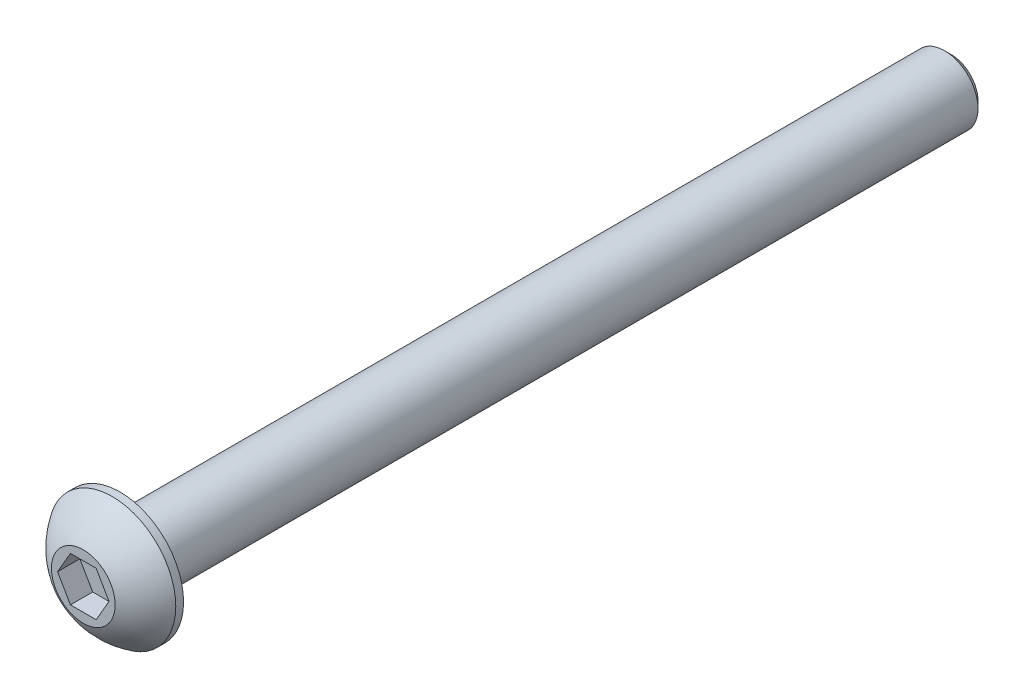
SolidWorks part; units mm, degrees
ref_plane "前视基准面" through (0, 0, 0) normal (0, 0, 1) x (1, 0, 0)
ref_plane "上视基准面" through (0, 0, 0) normal (0, 1, 0) x (1, 0, 0)
ref_plane "右视基准面" through (0, 0, 0) normal (1, 0, 0) x (0, 0, -1)
sketch "草图1" plane through (0, 0, 0) normal (1, 0, 0) x (0, 0, -1)
  line L0 (0, 1.5) -> (0, 2.85)
  line L1 (0, 2.85) -> (-0.35, 2.85)
  line L2 (0, 0) -> (-1.65, 0)
  line L3 (-1.65, 0) -> (-1.65, 1.43)
  line L4 (0, 0) -> (37.3, 0)
  line L5 (37.3, 0) -> (37.3, 1.5)
  line L6 (37.3, 1.5) -> (0, 1.5)
  arc A0 (-1.65, 1.43) -> (-0.35, 2.85) centre (1.5203, -0.1673) cw
  dimension "D4" = 3.55
  dimension "D1" = 2.85
  dimension "D2" = 0.35
  dimension "D3" = 1.43
  dimension "D5" = 1.65
  dimension "D6" = 37.3
  dimension "D7" = 1.5
revolve "旋转1" add sketch "草图1" angle 360 about L4
cosmetic thread "装饰螺纹线2"
sketch "草图2" plane through (0, 0, 1.65) normal (0, 0, 1) x (1, 0, 0)
  line L1 (-0.5774, 1) -> (-1.1547, 0)
  line L2 (-1.1547, 0) -> (-0.5774, -1)
  line L3 (-0.5774, -1) -> (0.5774, -1)
  line L4 (0.5774, -1) -> (1.1547, 0)
  line L5 (1.1547, 0) -> (0.5774, 1)
  line L6 (0.5774, 1) -> (-0.5774, 1)
  circle A0 centre (0, 0) radius 1 construction
  dimension "D1" = 1
extrude "切除-拉伸1" cut sketch "草图2" against normal blind 1
chamfer "倒角2" distance 0.3 angle 45 1 edges at (1.5, 0, -37.3)
